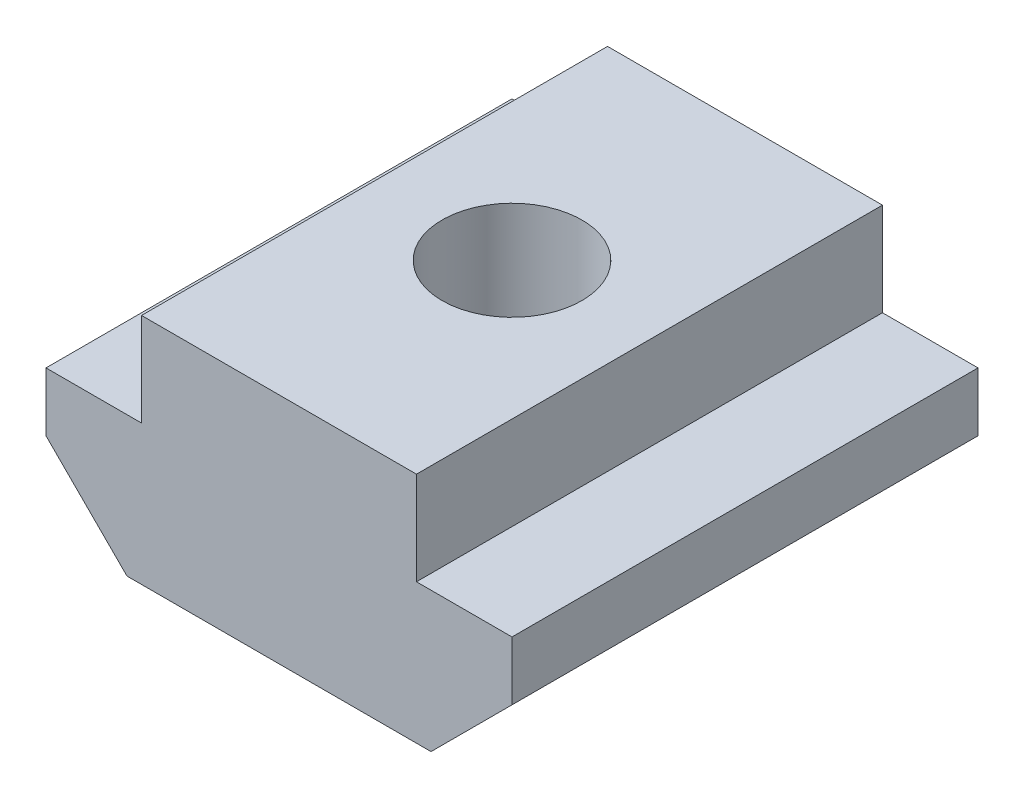
SolidWorks part; units mm, degrees
ref_plane "Plan de face" through (0, 0, 0) normal (0, 0, 1) x (1, 0, 0)
ref_plane "Plan de dessus" through (0, 0, 0) normal (0, 1, 0) x (1, 0, 0)
ref_plane "Plan de droite" through (0, 0, 0) normal (1, 0, 0) x (0, 0, -1)
sketch "Esquisse1" plane through (0, 0, 0) normal (0, 0, 1) x (1, 0, 0)
  line L0 (-10.5061, -2.0861) -> (-3.9814, -2.0861)
  line L1 (-3.9814, -2.0861) -> (-2.2437, -0.3484)
  line L2 (-2.2437, -0.3484) -> (-2.2437, 0.9139)
  line L3 (-2.2437, 0.9139) -> (-4.2937, 0.9139)
  line L4 (-4.2937, 0.9139) -> (-4.2937, 2.9139)
  line L5 (-4.2937, 2.9139) -> (-10.1937, 2.9139)
  line L6 (-10.1937, 2.9139) -> (-10.1937, 0.9139)
  line L7 (-10.1937, 0.9139) -> (-12.2437, 0.9139)
  line L8 (-12.2437, 0.9139) -> (-12.2437, -0.3484)
  line L9 (-12.2437, -0.3484) -> (-10.5061, -2.0861)
  point P2 (-7.2437, -2.0861)
  point P11 (-7.2437, 2.9139)
  dimension "D1" = 5.9
  dimension "D2" = 5
  dimension "D3" = 10
  dimension "D4" = 3
  dimension "D5" = 135
extrude "Boss.-Extru.1" add sketch "Esquisse1" along normal blind 10
sketch "Esquisse2" plane through (0, 2.9139, 0) normal (0, 1, 0) x (1, 0, 0)
  line L0 (-4.2937, -10) -> (-10.1937, -10) construction
  line L1 (-4.2937, -10) -> (-4.2937, 0) construction
  circle A0 centre (-7.2437, -5) radius 1.5
  point P5 (-7.2437, -10)
  point P8 (-4.2937, -5)
  dimension "D1" = 3
extrude "Enlèv. mat.-Extru.1" cut sketch "Esquisse2" against normal up to next
